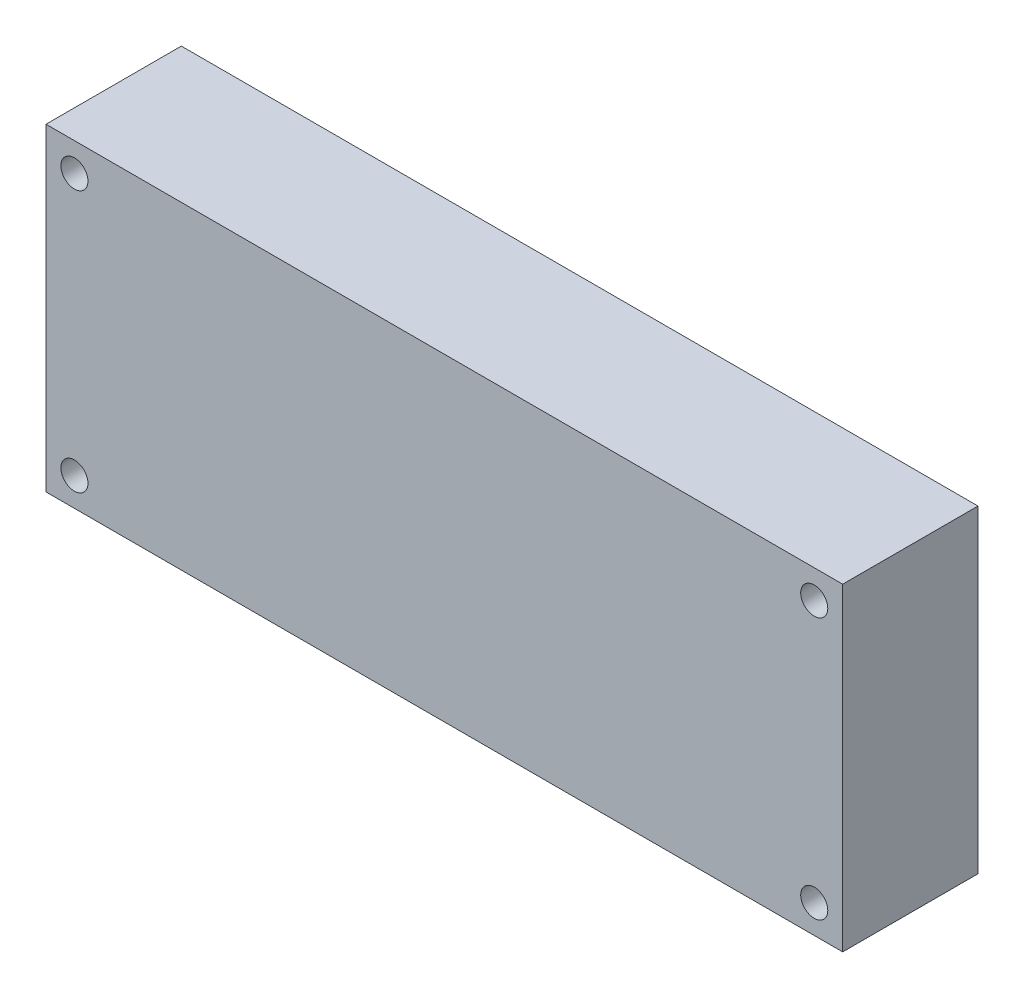
SolidWorks part; units mm, degrees
ref_plane "前基準面" through (0, 0, 0) normal (0, 0, 1) x (1, 0, 0)
ref_plane "上基準面" through (0, 0, 0) normal (0, 1, 0) x (1, 0, 0)
ref_plane "右基準面" through (0, 0, 0) normal (1, 0, 0) x (0, 0, -1)
sketch "草圖1" plane through (0, 0, 0) normal (0, 0, 1) x (1, 0, 0)
  line L1 (-44.15, 17.65) -> (44.15, 17.65)
  line L2 (-44.15, 17.65) -> (-44.15, -17.65)
  line L3 (-44.15, -17.65) -> (44.15, -17.65)
  line L4 (44.15, 17.65) -> (44.15, -17.65)
  line L5 (-44.15, 17.65) -> (44.15, -17.65) construction
  line L6 (-44.15, -17.65) -> (44.15, 17.65) construction
  line L7 (-41, 14.5) -> (41, 14.5) construction
  line L8 (-41, 14.5) -> (-41, -14.5) construction
  line L9 (-41, -14.5) -> (41, -14.5) construction
  line L10 (41, 14.5) -> (41, -14.5) construction
  line L11 (-41, 14.5) -> (41, -14.5) construction
  line L12 (-41, -14.5) -> (41, 14.5) construction
  circle A0 centre (-41, 14.5) radius 1.5
  circle A1 centre (-41, -14.5) radius 1.5
  circle A2 centre (41, -14.5) radius 1.5
  circle A3 centre (41, 14.5) radius 1.5
  point P0 (0, 0)
  point P6 (0, 0)
  dimension "D5" = 3
  dimension "D1" = 88.3
  dimension "D2" = 35.3
  dimension "D3" = 29
  dimension "D4" = 82
extrude "伸長1" add sketch "草圖1" along normal blind 15
